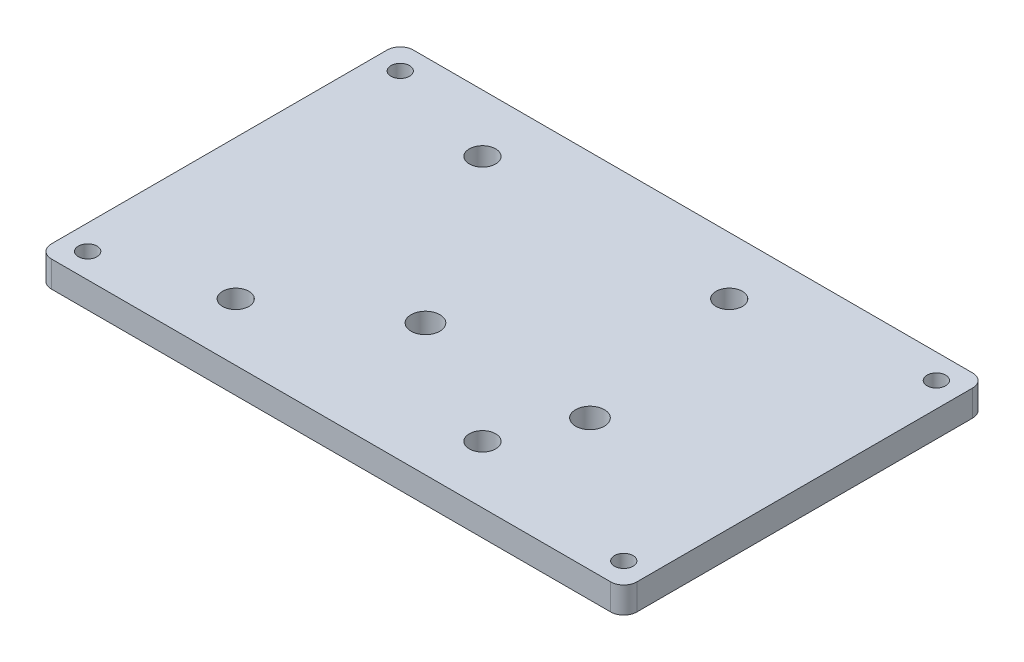
SolidWorks part; units mm, degrees
material "AISI 4130 Steel, annealed at 865C"
ref_plane "Front Plane" through (0, 0, 0) normal (0, 0, 1) x (1, 0, 0)
ref_plane "Top Plane" through (0, 0, 0) normal (0, 1, 0) x (1, 0, 0)
ref_plane "Right Plane" through (0, 0, 0) normal (1, 0, 0) x (0, 0, -1)
sketch "Sketch1" plane through (0, 0, 0) normal (0, 1, 0) x (1, 0, 0)
  line L0 (7, -7) -> (7, -37) construction
  line L1 (0, 0) -> (44, 0)
  line L2 (0, 0) -> (0, -44)
  line L3 (0, -44) -> (44, -44)
  line L4 (44, 0) -> (44, -44)
  line L5 (37, -7) -> (7, -7) construction
  line L7 (22, 0) -> (22, -44) construction
  line L8 (44, 0) -> (51.18, 0)
  line L9 (51.18, 0) -> (51.18, -44)
  line L10 (51.18, -44) -> (44, -44)
  line L11 (22, -22) -> (-15.2405, -22) construction
  line L12 (21.07, -28) -> (41.07, -28) construction
  circle A0 centre (7, -7) radius 1.6
  circle A1 centre (37, -7) radius 1.6
  circle A2 centre (37, -37) radius 1.6
  circle A3 centre (7, -37) radius 1.6
  circle A8 centre (21.07, -28) radius 1.75
  circle A9 centre (41.07, -28) radius 1.75
  dimension "D1" = 3.2
  dimension "D13" = 3.5
  dimension "D3" = 30
  dimension "D4" = 30
  dimension "D6" = 44
  dimension "D7" = 44
  dimension "D8" = 7
  dimension "D9" = 7
  dimension "D11" = 7.18
  dimension "D14" = 20
  dimension "D5" = 0.93
  dimension "D2" = 6
extrude "Boss-Extrude1" add sketch "Sketch1" along normal blind 3.175
sketch "Sketch2" plane through (0, 3.175, 0) normal (0, 1, 0) x (1, 0, 0)
  line L1 (0, 0) -> (-10, 0)
  line L2 (0, 0) -> (0, -44)
  line L3 (0, -44) -> (-10, -44)
  line L4 (-10, 0) -> (-10, -44)
  line L5 (51.18, 0) -> (61.18, 0)
  line L6 (51.18, 0) -> (51.18, -44)
  line L7 (51.18, -44) -> (61.18, -44)
  line L8 (61.18, 0) -> (61.18, -44)
  point P10 (58.18, -3)
  point P12 (58.18, -41)
  point P14 (-7, -3)
  point P15 (-7, -41)
  line M16 (51.18, -44) -> (51.18, 0)
  line M18 (0, 0) -> (0, -44)
  dimension "D1" = 10
  dimension "D2" = 3
  dimension "D3" = 3
  dimension "D4" = 3
  dimension "D5" = 3
extrude "Boss-Extrude2" add sketch "Sketch2" against normal up to surface (3.175 mm away) contours L1 L4 L3 M18 | L8 L5 L7 M16 up to face at (41.07, 0, 29.75)
hole_wizard "#4-40 Tapped Hole1" positions "3DSketch1" profile "Sketch3" tap size "#4-40" standard "ANSI Inch" end condition through all
sketch3d "3DSketch1"
  point P3 (-7, 3.175, 3)
  point P6 (-7, 3.175, 41)
  point P9 (58.18, 3.175, 3)
  point P12 (58.18, 3.175, 41)
sketch "Sketch3" plane through (-7, 3.175, 3) normal (1, 0, 0) x (0, 0, 1)
  line L0 (0, 0) -> (0, 3.175)
  line L1 (0, 3.175) -> (1.1303, 3.175)
  line L2 (1.1303, 3.175) -> (1.1303, 0)
  line L5 (1.1303, 0) -> (0, 0)
  line L11 (0, -6.35) -> (0, 107.95) construction
  dimension "Thru Tap Drill Dia." = 2.2606
  dimension "Thru Tap Drill Depth" = 3.175
cosmetic thread "Hole Thread1" parameters "D2"=2.8448
cosmetic thread "Hole Thread2" parameters "D2"=2.8448
cosmetic thread "Hole Thread3" parameters "D2"=2.8448
cosmetic thread "Hole Thread4" parameters "D2"=2.8448
fillet "Fillet2" radius 1.5875 4 edges at (-10, 1.5875, 0) (61.18, 1.5875, 0) (61.18, 1.5875, 44) (-10, 1.5875, 44)
equation "\"D8@Sketch1\"=(\"D7@Sketch1\"-\"D4@Sketch1\")/2"
equation "\"D9@Sketch1\"=\"D8@Sketch1\""
equation "\"D3@Sketch2\"=\"D2@Sketch2\""
equation "\"D4@Sketch2\"=\"D2@Sketch2\""
equation "\"D5@Sketch2\"=\"D2@Sketch2\""
equation "\"D5@Sketch1\"=9.37mm-6.3-2-0.14"
